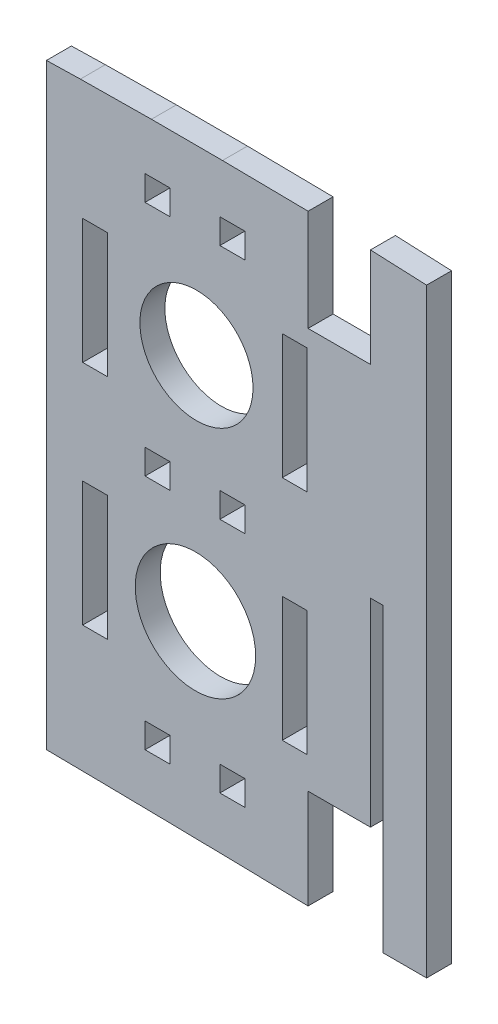
SolidWorks part; units mm, degrees
ref_plane "前视基准面" through (0, 0, 0) normal (0, 0, 1) x (1, 0, 0)
ref_plane "上视基准面" through (0, 0, 0) normal (0, 1, 0) x (1, 0, 0)
ref_plane "右视基准面" through (0, 0, 0) normal (1, 0, 0) x (0, 0, -1)
sketch "Model" plane through (0, 0, 0) normal (0, 0, 1) x (1, 0, 0)
  line L0 (883.6372, 587.3305) -> (886.3566, 587.3934)
  line L1 (886.3566, 587.3934) -> (892.0524, 587.4529)
  line L2 (892.0524, 587.4529) -> (897.7484, 587.4383)
  line L3 (894.1404, 539.3311) -> (888.4441, 539.4208)
  line L4 (888.4441, 539.4208) -> (883.6369, 539.4811)
  line L5 (904.6088, 539.1172) -> (899.8355, 539.2235)
  line L6 (897.7484, 587.4383) -> (904.6088, 587.3486)
  line L7 (899.8355, 539.2235) -> (894.1404, 539.3311)
  line L8 (909.6088, 587.1614) -> (909.6088, 580.2112)
  line L9 (883.6372, 541.525) -> (883.6369, 539.4811)
  line L10 (910.6088, 538.869) -> (910.6088, 562.993)
  line L11 (910.6088, 562.993) -> (909.6088, 562.993)
  line L12 (914.1088, 538.869) -> (910.6088, 538.869)
  line L13 (909.6088, 587.1614) -> (914.1088, 586.967)
  line L14 (883.6372, 541.525) -> (883.6372, 587.3305)
  line L15 (886.5404, 549.5848) -> (888.5404, 549.5848)
  line L16 (888.5404, 549.5848) -> (888.5404, 559.5848)
  line L17 (888.5404, 559.5848) -> (886.5404, 559.5848)
  line L18 (886.5404, 559.5848) -> (886.5404, 549.5848)
  line L19 (886.5404, 567.8179) -> (888.5404, 567.8179)
  line L20 (888.5404, 567.8179) -> (888.5404, 577.8179)
  line L21 (888.5404, 577.8179) -> (886.5404, 577.8179)
  line L22 (886.5404, 577.8179) -> (886.5404, 567.8179)
  line L23 (904.5404, 577.8179) -> (902.5404, 577.8179)
  line L24 (902.5404, 577.8179) -> (902.5404, 567.8179)
  line L25 (902.5404, 567.8179) -> (904.5404, 567.8179)
  line L26 (904.5404, 567.8179) -> (904.5404, 577.8179)
  line L27 (904.5404, 559.5848) -> (902.5404, 559.5848)
  line L28 (902.5404, 559.5848) -> (902.5404, 549.5848)
  line L29 (902.5404, 549.5848) -> (904.5404, 549.5848)
  line L30 (904.5404, 549.5848) -> (904.5404, 559.5848)
  line L31 (897.5404, 543.4289) -> (899.5404, 543.4289)
  line L32 (899.5404, 543.4289) -> (899.5404, 545.4289)
  line L33 (899.5404, 545.4289) -> (897.5404, 545.4289)
  line L34 (897.5404, 545.4289) -> (897.5404, 543.4289)
  line L35 (893.5404, 543.4289) -> (891.5404, 543.4289)
  line L36 (891.5404, 543.4289) -> (891.5404, 545.4289)
  line L37 (891.5404, 545.4289) -> (893.5404, 545.4289)
  line L38 (893.5404, 545.4289) -> (893.5404, 543.4289)
  line L39 (897.5404, 562.4289) -> (899.5404, 562.4289)
  line L40 (899.5404, 562.4289) -> (899.5404, 564.4289)
  line L41 (899.5404, 564.4289) -> (897.5404, 564.4289)
  line L42 (897.5404, 564.4289) -> (897.5404, 562.4289)
  line L43 (893.5404, 562.4289) -> (891.5404, 562.4289)
  line L44 (891.5404, 562.4289) -> (891.5404, 564.4289)
  line L45 (891.5404, 564.4289) -> (893.5404, 564.4289)
  line L46 (893.5404, 564.4289) -> (893.5404, 562.4289)
  line L47 (897.5404, 581.4289) -> (899.5404, 581.4289)
  line L48 (899.5404, 581.4289) -> (899.5404, 583.4289)
  line L49 (899.5404, 583.4289) -> (897.5404, 583.4289)
  line L50 (897.5404, 583.4289) -> (897.5404, 581.4289)
  line L51 (893.5404, 581.4289) -> (891.5404, 581.4289)
  line L52 (891.5404, 581.4289) -> (891.5404, 583.4289)
  line L53 (891.5404, 583.4289) -> (893.5404, 583.4289)
  line L54 (893.5404, 583.4289) -> (893.5404, 581.4289)
  line L55 (914.1088, 579.8595) -> (914.1088, 586.967)
  line L56 (909.6088, 580.2112) -> (909.6088, 579.2112)
  line L57 (909.6088, 579.2112) -> (904.6088, 579.2112)
  line L58 (909.6088, 547.0866) -> (904.6088, 547.0866)
  line L59 (904.6088, 579.2112) -> (904.6088, 587.3486)
  line L60 (904.6088, 547.0866) -> (904.6088, 539.1172)
  line L61 (914.1088, 579.8595) -> (914.1088, 538.869)
  line L62 (909.6088, 547.0866) -> (909.6088, 562.993)
  circle A0 centre (895.6619, 572.8658) radius 4.5344
  circle A1 centre (895.5796, 554.3628) radius 4.8269
extrude "凸台-拉伸1" add sketch "Model" along normal blind 2
